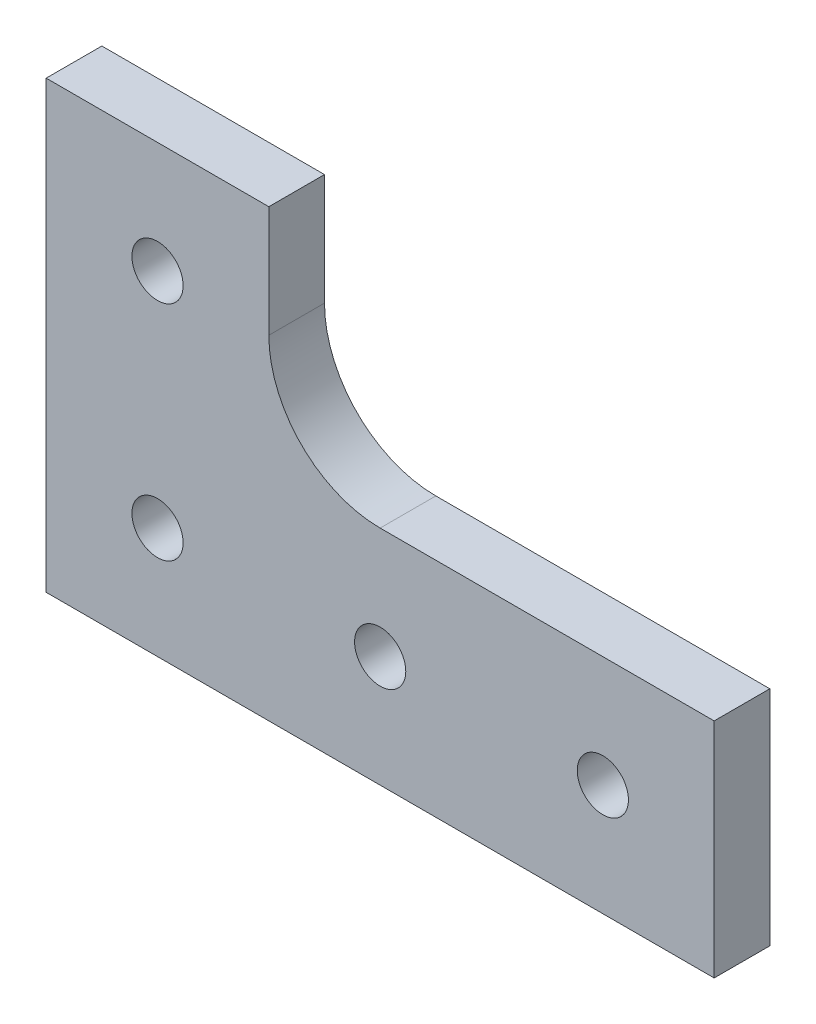
SolidWorks part; units mm, degrees
ref_plane "Front Plane" through (0, 0, 0) normal (0, 0, 1) x (1, 0, 0)
ref_plane "Top Plane" through (0, 0, 0) normal (0, 1, 0) x (1, 0, 0)
ref_plane "Right Plane" through (0, 0, 0) normal (1, 0, 0) x (0, 0, -1)
sketch "Sketch1" plane through (0, 0, 0) normal (0, 0, 1) x (1, 0, 0)
  line L0 (0, 0) -> (0, 50.8)
  line L1 (0, 50.8) -> (25.4, 50.8)
  line L2 (25.4, 50.8) -> (25.4, 25.4)
  line L3 (25.4, 25.4) -> (76.2, 25.4)
  line L4 (76.2, 25.4) -> (76.2, 0)
  line L5 (76.2, 0) -> (0, 0)
  dimension "D1" = 50.8
  dimension "D2" = 25.4
  dimension "3" = 76.2
extrude "Boss-Extrude1" add sketch "Sketch1" along normal blind 6.35
sketch "Sketch2" plane through (0, 0, 6.35) normal (0, 0, 1) x (1, 0, 0)
  line L0 (25.4, 50.8) -> (0, 50.8) construction
  line L1 (25.4, 25.4) -> (25.4, 50.8) construction
  line L2 (0, 0) -> (76.2, 0) construction
  circle A0 centre (12.7, 38.1) radius 2.921
  circle A1 centre (12.7, 12.7) radius 2.921
  circle A2 centre (38.1, 12.7) radius 2.921
  circle A3 centre (63.5, 12.7) radius 2.921
  dimension "D1" = 5.842
  dimension "D2" = 12.7
  dimension "D3" = 12.7
  dimension "D4" = 12.7
  dimension "D5" = 3
extrude "Cut-Extrude1" cut sketch "Sketch2" against normal through all
fillet "Fillet1" radius 12.7 1 edges at (25.4, 25.4, 3.175)
